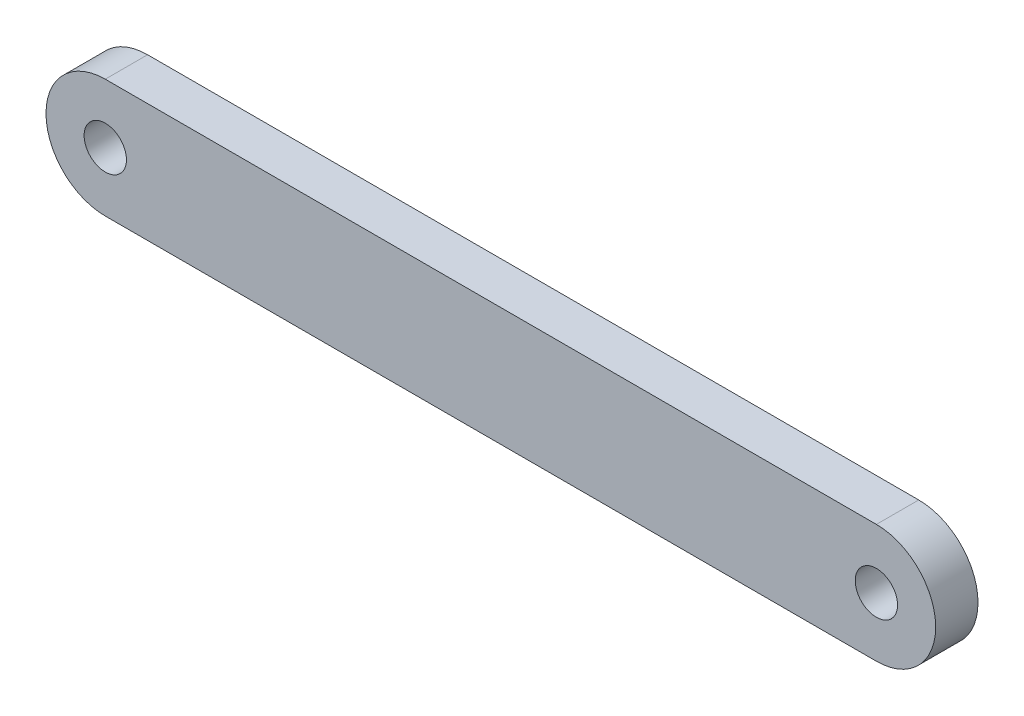
SolidWorks part; units mm, degrees
ref_plane "Front Plane" through (0, 0, 0) normal (0, 0, 1) x (1, 0, 0)
ref_plane "Top Plane" through (0, 0, 0) normal (0, 1, 0) x (1, 0, 0)
ref_plane "Right Plane" through (0, 0, 0) normal (1, 0, 0) x (0, 0, -1)
sketch "Sketch1" plane through (0, 0, 0) normal (0, 0, 1) x (1, 0, 0)
  line L0 (-49.4442, -8.7733) -> (66.2274, -8.7733)
  line L1 (-49.4442, 9.0067) -> (66.2274, 9.0067)
  line L2 (-49.4442, -8.7733) -> (66.2274, 9.0067) construction
  line L3 (-49.4442, 9.0067) -> (66.2274, -8.7733) construction
  arc A0 (-49.4442, 9.0067) -> (-49.4442, -8.7733) centre (-49.4442, 0.1167) ccw
  arc A1 (66.2274, 9.0067) -> (66.2274, -8.7733) centre (66.2274, 0.1167) cw
  circle A2 centre (-49.4442, 0.1167) radius 3.175
  circle A3 centre (66.2274, 0.1167) radius 3.175
  point P0 (8.3916, 0.1167)
  dimension "D3" = 6.35
  dimension "D1" = 115.6716
  dimension "D2" = 17.78
extrude "Boss-Extrude1" add sketch "Sketch1" along normal blind 6.35
